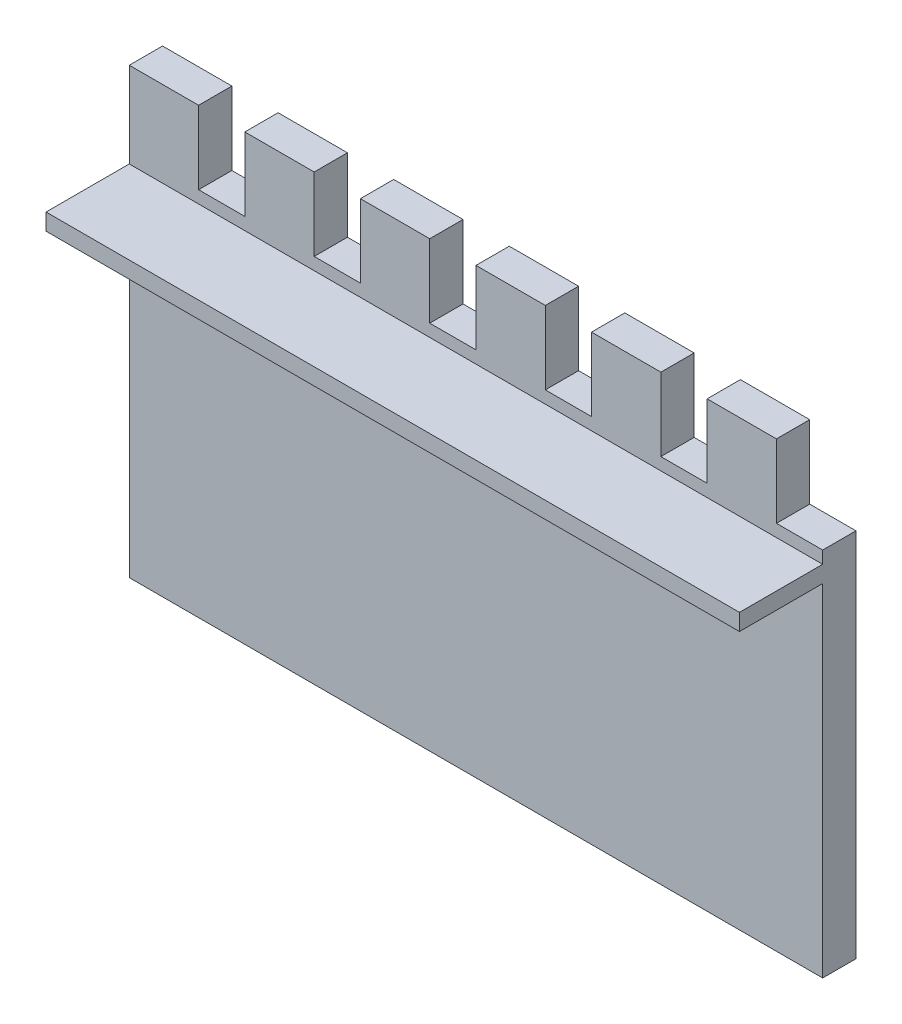
SolidWorks part; units mm, degrees
ref_plane "Front Plane" through (0, 0, 0) normal (0, 0, 1) x (1, 0, 0)
ref_plane "Top Plane" through (0, 0, 0) normal (0, 1, 0) x (1, 0, 0)
ref_plane "Right Plane" through (0, 0, 0) normal (1, 0, 0) x (0, 0, -1)
sketch "Sketch1" plane through (0, 0, 0) normal (0, 0, 1) x (1, 0, 0)
  line L1 (0, 0) -> (38100, 0)
  line L2 (0, 0) -> (0, 24384)
  line L3 (0, 24384) -> (38100, 24384)
  line L4 (38100, 0) -> (38100, 24384)
  dimension "D1" = 38100
  dimension "D2" = 24384
extrude "Boss-Extrude1" add sketch "Sketch1" along normal blind 1828.8
sketch "Sketch2" plane through (0, 0, 1828.8) normal (0, 0, 1) x (1, 0, 0)
  line L0 (0, 24384) -> (0, 20364.7506)
  line L1 (0, 24384) -> (0, 0) construction
  line L2 (0, 20364.7506) -> (3810, 20364.7506)
  line L3 (3810, 20364.7506) -> (3810, 24384)
  line L4 (38100, 24384) -> (0, 24384) construction
  line L5 (3810, 24384) -> (0, 24384)
  line L6 (6350, 24384) -> (6350, 20364.7506)
  line L7 (6350, 20364.7506) -> (10160, 20364.7506)
  line L8 (10160, 20364.7506) -> (10160, 24384)
  line L9 (10160, 24384) -> (6350, 24384)
  line L10 (11430, 24384) -> (12700, 24384)
  line L11 (16510, 24384) -> (19050, 24384)
  line L12 (16510, 24384) -> (19050, 24384)
  line L13 (6350, 24384) -> (11430, 24384)
  line L14 (19050, 24384) -> (19050, 20364.7506)
  line L15 (19050, 20364.7506) -> (22860, 20364.7506)
  line L16 (22860, 20364.7506) -> (22860, 24384)
  line L17 (22860, 24384) -> (19050, 24384)
  line L18 (25400, 24384) -> (25400, 20364.7506)
  line L19 (25400, 20364.7506) -> (29210, 20364.7506)
  line L20 (29210, 20364.7506) -> (29210, 24384)
  line L21 (29210, 24384) -> (25400, 24384)
  line L22 (31750, 24384) -> (31750, 20364.7506)
  line L23 (31750, 24384) -> (35560, 24384)
  line L24 (38100, 20364.7506) -> (38100, 24384)
  line L25 (3810, 20364.7506) -> (6350, 20364.7506)
  line L26 (3810, 24384) -> (6350, 24384)
  line L27 (10160, 24384) -> (11430, 24384)
  line L28 (11430, 24384) -> (10160, 24384)
  line L29 (16510, 24384) -> (19050, 24384)
  line L30 (22860, 24384) -> (25400, 24384)
  line L31 (10160, 24384) -> (12700, 24384)
  line L32 (16510, 24384) -> (19050, 24384)
  line L33 (12700, 24384) -> (16510, 24384)
  line L34 (12700, 24384) -> (12700, 20364.7506)
  line L35 (12700, 20364.7506) -> (16510, 20364.7506)
  line L36 (16510, 24384) -> (16510, 20364.7506)
  line L37 (6350, 24384) -> (12700, 24384)
  line L38 (22860, 24384) -> (25400, 24384)
  line L39 (12700, 20364.7506) -> (10160, 20364.7506)
  line L40 (22860, 24384) -> (25400, 24384)
  line L41 (29210, 24384) -> (31750, 24384)
  line L42 (35560, 20364.7506) -> (35560, 24384)
  line L43 (31750, 20364.7506) -> (35560, 20364.7506)
  line L44 (16510, 20364.7506) -> (19050, 20364.7506)
  line L45 (19050, 24384) -> (16510, 24384)
  line L46 (22860, 24384) -> (25400, 24384)
  line L47 (25400, 20364.7506) -> (22860, 20364.7506)
  line L48 (29210, 20364.7506) -> (31750, 20364.7506)
  line L49 (31750, 24384) -> (29210, 24384)
  line L50 (35560, 24384) -> (38100, 24384)
  line L51 (38100, 20364.7506) -> (35560, 20364.7506)
  line L52 (38100, 20364.7506) -> (38100, 24384)
  line M3 (38100, 0) -> (38100, 24384)
  line M4 (38100, 24384) -> (0, 24384)
  dimension "D1" = 2540
  dimension "D2" = 2540
  dimension "D3" = 2540
  dimension "D5" = 3810
extrude "Cut-Extrude2" cut sketch "Sketch2" against normal blind 1828.8 contours L3 L25 L6 M4 | L39 L34 L8 M4 | L36 L44 L14 M4 | L47 L18 L16 M4 | L20 L48 L22 M4 | L51 L42 M3 M4
sketch "Sketch3" plane through (0, 0, 1828.8) normal (0, 0, 1) x (1, 0, 0)
  line L0 (0, 19685.709) -> (38100, 19685.709)
  line L1 (0, 24384) -> (0, 0) construction
  line L2 (38100, 0) -> (38100, 20364.7506) construction
  line L3 (38100, 19685.709) -> (38100, 18771.309)
  line L4 (38100, 18771.309) -> (0, 18771.309)
  line L5 (0, 18771.309) -> (0, 19685.709)
  dimension "D1" = 914.4
extrude "Boss-Extrude3" add sketch "Sketch3" along normal blind 4572
